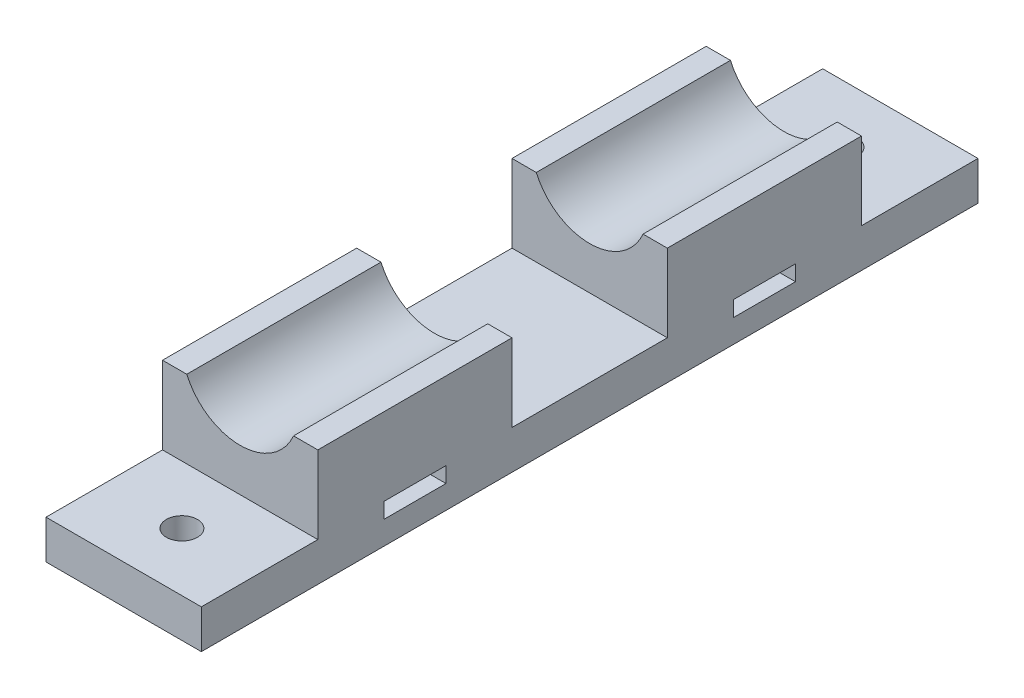
SolidWorks part; units mm, degrees
material "ABS"
ref_plane "Plano frontal" through (0, 0, 0) normal (0, 0, 1) x (1, 0, 0)
ref_plane "Plano superior" through (0, 0, 0) normal (0, 1, 0) x (1, 0, 0)
ref_plane "Plano direito" through (0, 0, 0) normal (1, 0, 0) x (0, 0, -1)
sketch "Esboço1" plane through (0, 0, 0) normal (1, 0, 0) x (0, 0, -1)
  line L0 (0, 14) -> (0, 0) construction
  line L1 (-35, 18) -> (-10, 18)
  line L2 (-35, 18) -> (-35, 0)
  line L3 (-35, 0) -> (35, 0)
  line L4 (35, 18) -> (35, 0)
  line L5 (18.5, 3) -> (26.5, 5) construction
  line L6 (-18.5, 5) -> (-26.5, 5)
  line L7 (-18.5, 5) -> (-18.5, 3)
  line L8 (-18.5, 3) -> (-26.5, 3)
  line L9 (-10, 18) -> (-10, 5)
  line L10 (-26.5, 5) -> (-26.5, 3)
  line L11 (-18.5, 5) -> (-26.5, 3) construction
  line L12 (-18.5, 3) -> (-26.5, 5) construction
  line L13 (18.5, 5) -> (26.5, 3) construction
  line L14 (-10, 5) -> (10, 5)
  line L15 (10, 18) -> (10, 5)
  line L16 (10, 18) -> (35, 18)
  line L17 (26.5, 5) -> (26.5, 3)
  line L18 (18.5, 3) -> (26.5, 3)
  line L19 (18.5, 5) -> (18.5, 3)
  line L20 (18.5, 5) -> (26.5, 5)
  point P0 (0, 0)
  point P1 (-22.5, 4)
  point P18 (0, 5)
  point P21 (22.5, 4)
  point P24 (-22.5, 18)
  dimension "D1" = 8
  dimension "D2" = 18
  dimension "D3" = 70
  dimension "D4" = 2
  dimension "D5" = 25
  dimension "D6" = 5
  dimension "D7" = 4
extrude "Ressalto-extrusão1" add sketch "Esboço1" along normal mid plane 20
sketch "Esboço2" plane through (0, 0, 35) normal (0, 0, 1) x (1, 0, 0)
  line L0 (10, 18) -> (-10, 18) construction
  line L1 (-10, 15) -> (-6.8739, 15)
  line L2 (0, 18) -> (-7.5, 18) construction
  line L3 (-7.5, 18) -> (7.5, 18)
  line L4 (-10, 18) -> (-10, 0) construction
  line L5 (10, 18) -> (10, 0) construction
  line L6 (-10, 15) -> (-10, 18)
  line L7 (-10, 18) -> (-7.5, 18)
  line L8 (7.5, 18) -> (10, 18)
  line L9 (10, 18) -> (10, 15)
  line L10 (6.8739, 15) -> (10, 15)
  arc A0 (-6.8739, 15) -> (6.8739, 15) centre (0, 18) ccw
  point P7 (0, 18)
  dimension "D1" = 15
  dimension "D2" = 3
extrude "Corte-extrusão1" cut sketch "Esboço2" against normal up to surface (70 mm away) up to face at (0, 9, -35)
sketch "Esboço4" plane through (0, 5, 0) normal (0, 1, 0) x (1, 0, 0)
  line L1 (-10, 0) -> (10, 0) construction
  line L2 (-10, 35) -> (10, 35)
  line L3 (-10, 35) -> (-10, 50)
  line L4 (-10, 50) -> (10, 50)
  line L5 (10, -35) -> (10, -50)
  line L6 (10, 35) -> (10, 50)
  line L7 (-10, -50) -> (10, -50)
  line L8 (-10, 10) -> (-10, -10) construction
  line L9 (10, 10) -> (10, -10) construction
  line L10 (-10, -35) -> (-10, -50)
  line L11 (-10, -35) -> (10, -35)
  line L12 (10, -35) -> (10, 35) construction
  circle A0 centre (0, 42.5) radius 2
  circle A1 centre (0, -42.5) radius 2
  point P7 (0, 0)
  point P8 (0, 0)
  point P13 (0, 50)
  dimension "D3" = 7.5
  dimension "D2" = 4
  dimension "D1" = 100
extrude "Ressalto-extrusão2" add sketch "Esboço4" against normal up to surface (5 mm away) up to face at (0, 0, 0)
